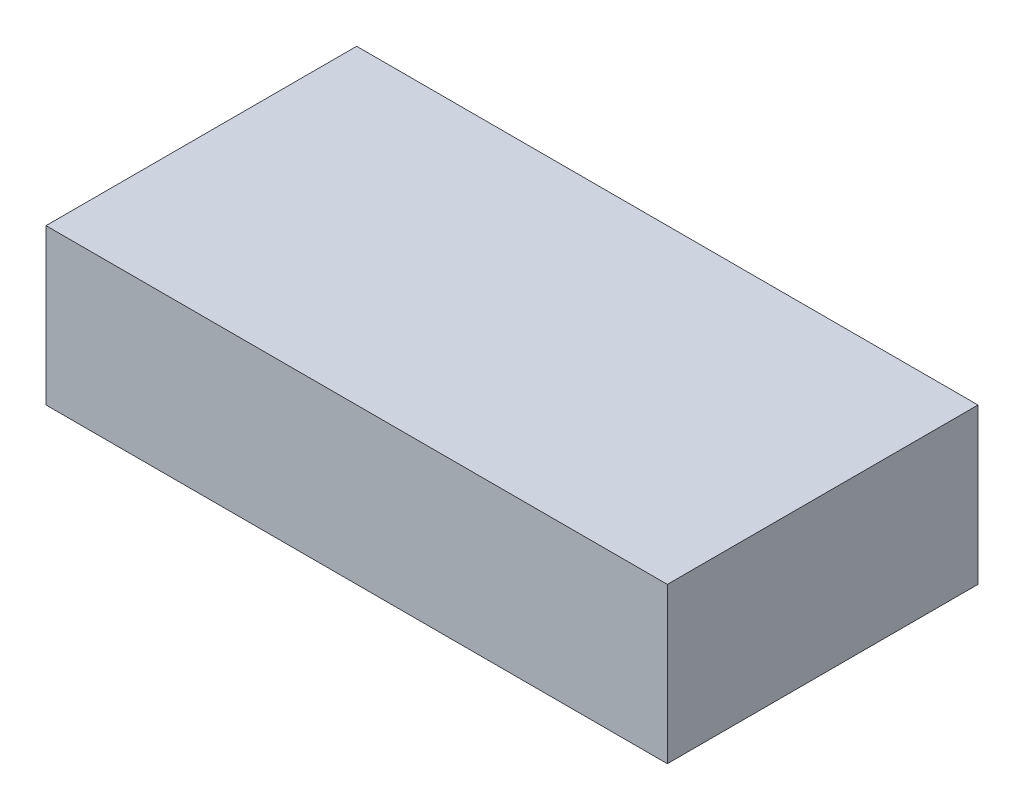
SolidWorks part; units mm, degrees
ref_plane "정면" through (0, 0, 0) normal (0, 0, 1) x (1, 0, 0)
ref_plane "윗면" through (0, 0, 0) normal (0, 1, 0) x (1, 0, 0)
ref_plane "우측면" through (0, 0, 0) normal (1, 0, 0) x (0, 0, -1)
sketch "스케치1" plane through (0, 0, 0) normal (0, 0, 1) x (1, 0, 0)
  line L1 (-10, -2.5) -> (10, -2.5)
  line L2 (-10, -2.5) -> (-10, 2.5)
  line L3 (-10, 2.5) -> (10, 2.5)
  line L4 (10, -2.5) -> (10, 2.5)
  line L5 (-10, -2.5) -> (10, 2.5) construction
  line L6 (-10, 2.5) -> (10, -2.5) construction
  point P0 (0, 0)
  dimension "D1" = 5
  dimension "D2" = 20
extrude "보스-돌출1" add sketch "스케치1" along normal blind 10
